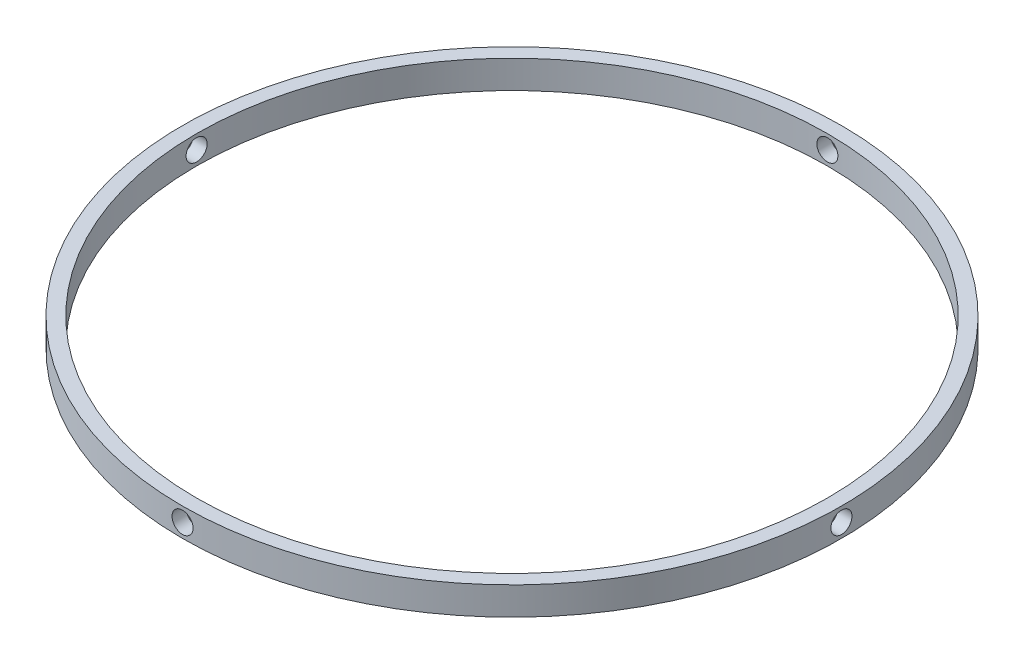
SolidWorks part; units mm, degrees
ref_plane "Front Plane" through (0, 0, 0) normal (0, 0, 1) x (1, 0, 0)
ref_plane "Top Plane" through (0, 0, 0) normal (0, 1, 0) x (1, 0, 0)
ref_plane "Right Plane" through (0, 0, 0) normal (1, 0, 0) x (0, 0, -1)
sketch "Sketch1" plane through (0, 0, 0) normal (0, 1, 0) x (1, 0, 0)
  circle A0 centre (0, 0) radius 235
  circle A1 centre (0, 0) radius 225
  dimension "D1" = 470
  dimension "D2" = 450
extrude "Boss-Extrude1" add sketch "Sketch1" along normal blind 20
sketch "Sketch2" plane through (0, 0, 0) normal (0, 0, 1) x (1, 0, 0)
  line L0 (-235, 20) -> (235, 0) construction
  line L1 (-235, 0) -> (235, 20) construction
  circle A0 centre (0, 10) radius 7.5
  dimension "D1" = 15
extrude "Cut-Extrude1" cut sketch "Sketch2" against normal through all and the other way through all
sketch "Sketch3" plane through (0, 0, 0) normal (1, 0, 0) x (0, 0, -1)
  line L0 (-235, 20) -> (235, 0) construction
  line L1 (-235, 0) -> (235, 20) construction
  circle A0 centre (0, 10) radius 7.5
  dimension "D1" = 15
extrude "Cut-Extrude2" cut sketch "Sketch3" against normal through all both and the other way through all
ref_point "Point1"
ref_point "Point2"
ref_point "Point3"
